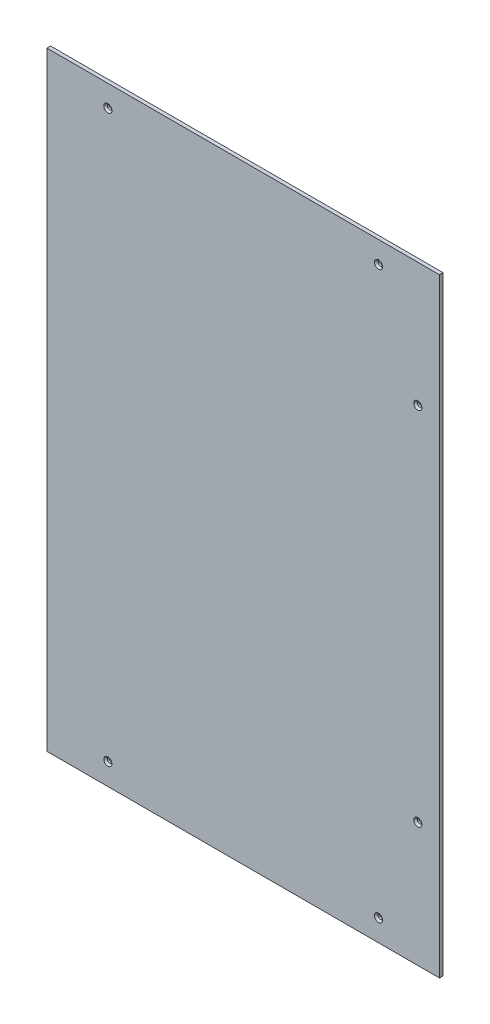
SolidWorks part; units mm, degrees
material "1.4301 (X5CrNi18-10)"
ref_plane "Plan de face" through (0, 0, 0) normal (0, 0, 1) x (1, 0, 0)
ref_plane "Plan de dessus" through (0, 0, 0) normal (0, 1, 0) x (1, 0, 0)
ref_plane "Plan de droite" through (0, 0, 0) normal (1, 0, 0) x (0, 0, -1)
sketch "Esquisse1" plane through (0, 0, 0) normal (0, 0, 1) x (1, 0, 0)
  line L1 (-217.5, -337.5) -> (217.5, -337.5)
  line L2 (-217.5, -337.5) -> (-217.5, 337.5)
  line L3 (-217.5, 337.5) -> (217.5, 337.5)
  line L4 (217.5, -337.5) -> (217.5, 337.5)
  line L5 (-217.5, -337.5) -> (217.5, 337.5) construction
  line L6 (-217.5, 337.5) -> (217.5, -337.5) construction
  point P0 (0, 0)
  dimension "D1" = 675
  dimension "D2" = 435
extrude "Boss.-Extru.1" add sketch "Esquisse1" along normal mid plane 4
sketch "Esquisse3" plane through (0, 0, 2) normal (0, 0, 1) x (1, 0, 0)
  line L0 (-193.5, 0) -> (193.5, 0) construction
  line L1 (193.5, -313.5) -> (-193.5, -313.5) construction
  line L2 (193.5, -313.5) -> (193.5, 313.5) construction
  line L3 (193.5, 313.5) -> (-193.5, 313.5) construction
  line L4 (-193.5, -313.5) -> (-193.5, 313.5) construction
  line L5 (193.5, -313.5) -> (-193.5, 313.5) construction
  line L6 (193.5, 313.5) -> (-193.5, -313.5) construction
  line L7 (0, -313.5) -> (0, 313.5) construction
  line L8 (-217.5, 337.5) -> (-217.5, -337.5) construction
  line L9 (-217.5, -337.5) -> (217.5, -337.5) construction
  circle A0 centre (-150, -313.5) radius 2.5
  circle A1 centre (150, -313.5) radius 2.5
  circle A2 centre (193.5, -200) radius 2.5
  circle A3 centre (193.5, 200) radius 2.5
  circle A4 centre (150, 313.5) radius 2.5
  circle A5 centre (-150, 313.5) radius 2.5
  point P0 (0, 0)
  dimension "D3" = 5
  dimension "D1" = 24
  dimension "D2" = 24
  dimension "D4" = 300
  dimension "D5" = 400
extrude "Enlèv. mat.-Extru.1" cut sketch "Esquisse3" against normal through all
chamfer "Chanfrein1" distance 2 angle 45 6 edges at (-147.5, 313.5, 2) (152.5, 313.5, 2) (196, 200, 2) (196, -200, 2) (152.5, -313.5, 2) (-147.5, -313.5, 2)
